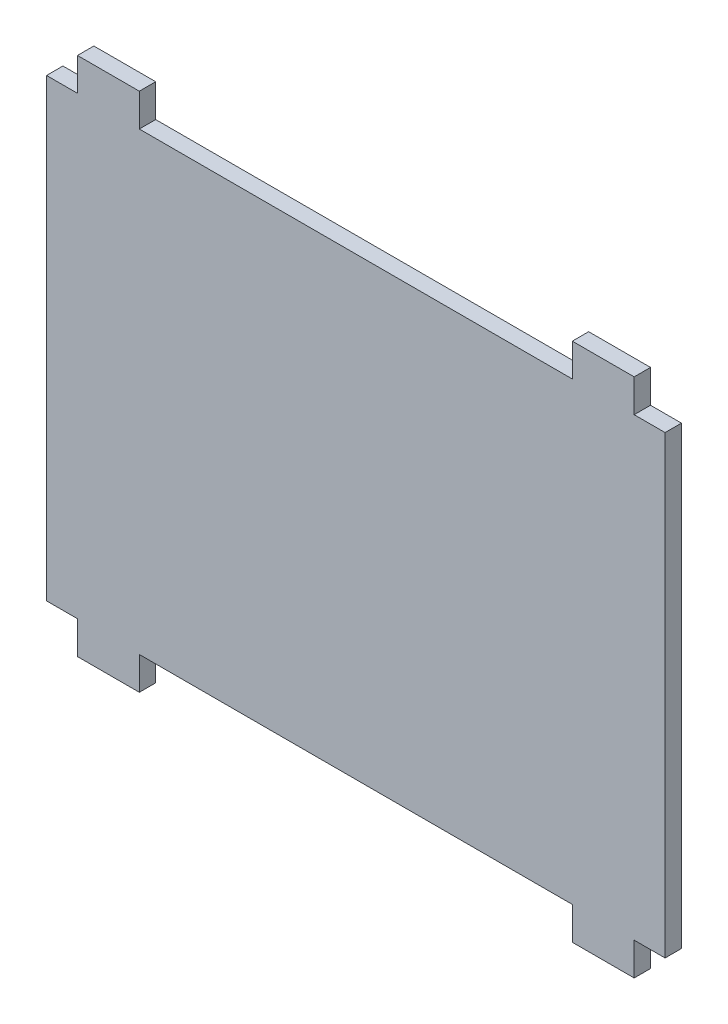
SolidWorks part; units mm, degrees
ref_plane "Front Plane" through (0, 0, 0) normal (0, 0, 1) x (1, 0, 0)
ref_plane "Top Plane" through (0, 0, 0) normal (0, 1, 0) x (1, 0, 0)
ref_plane "Right Plane" through (0, 0, 0) normal (1, 0, 0) x (0, 0, -1)
sketch "Sketch1" plane through (0, 0, 0) normal (0, 0, 1) x (1, 0, 0)
  line L0 (0.8731, 0) -> (-0.8731, 0) construction
  line L1 (-30, 0) -> (30, 0)
  line L2 (-30, 0) -> (-30, 25.25)
  line L3 (-30, 25.25) -> (30, 25.25)
  line L4 (30, 0) -> (30, 25.25)
  line L5 (0, -0.8731) -> (0, 0.8731) construction
  point P6 (0, 25.25)
  dimension "D1" = 60
  dimension "D2" = 25.25
extrude "Boss-Extrude1" add sketch "Sketch1" along normal blind 1.5875
sketch "Sketch2" plane through (0, 0, 1.5875) normal (0, 0, 1) x (1, 0, 0)
  line L0 (30, 25.25) -> (-30, 25.25) construction
  line L1 (-3.3, 25.25) -> (3.3, 25.25) construction
  line L5 (0, -0.8731) -> (0, 0.8731) construction
  line L22 (-21, 25.25) -> (21, 25.25)
  line L27 (-21, 25.25) -> (-21, 22.07)
  line L28 (-21, 22.07) -> (21, 22.07)
  line L29 (21, 25.25) -> (21, 22.07)
  line L30 (27, 25.25) -> (32.7, 25.25)
  line L31 (27, 25.25) -> (27, 22.07)
  line L32 (27, 22.07) -> (32.7, 22.07)
  line L33 (32.7, 25.25) -> (32.7, 22.07)
  line L42 (-32.8, 25.25) -> (-27, 25.25)
  line L43 (-32.8, 25.25) -> (-32.8, 22.07)
  line L44 (-32.8, 22.07) -> (-27, 22.07)
  line L45 (-27, 25.25) -> (-27, 22.07)
  line L46 (-27, 23.66) -> (-21, 23.66) construction
  line L47 (-21, 23.66) -> (-24, 23.66) construction
  line L48 (-24, 23.66) -> (-24, 25.25) construction
  line L49 (21, 23.66) -> (27, 23.66) construction
  line L50 (27, 23.66) -> (24, 23.66) construction
  line L51 (24, 23.66) -> (24, 25.25) construction
  point P6 (0, 25.25)
  point P21 (0, 0)
  point P24 (0, 0)
  point P25 (0, 0)
  point P26 (0, 0)
  point P27 (0, 0)
  point P32 (0, 0)
  point P33 (0, 0)
  point P34 (0, 0)
  dimension "D1" = 24
  dimension "D2" = 3.18
  dimension "D3" = 6
  dimension "D4" = 6
  dimension "D5" = 3.18
  dimension "D6" = 3.18
  dimension "D7" = 24
extrude "Cut-Extrude1" cut sketch "Sketch2" against normal blind 1.5875
mirror "Mirror1" about plane through (0, 0, 0) normal (0, 1, 0) of "Cut-Extrude1", "Boss-Extrude1"
